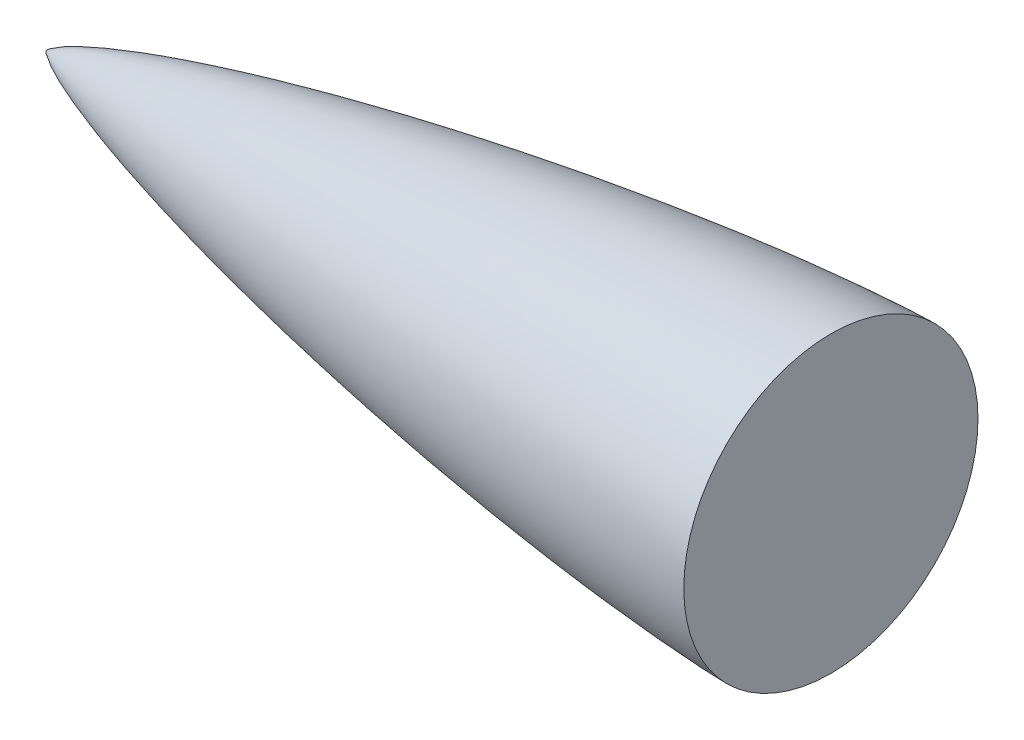
SolidWorks part; units mm, degrees
ref_plane "Front Plane" through (0, 0, 0) normal (0, 0, 1) x (1, 0, 0)
ref_plane "Top Plane" through (0, 0, 0) normal (0, 1, 0) x (1, 0, 0)
ref_plane "Right Plane" through (0, 0, 0) normal (1, 0, 0) x (0, 0, -1)
sketch "Sketch6" plane through (0, 0, 0) normal (0, 0, 1) x (1, 0, 0)
  line L0 (0, 0) -> (16, 0)
  line L1 (16, 3) -> (16, 0)
  spline S0 degree 4 poles (0, 0) (0.0011, 0.003) (0.0037, 0.008) (0.0089, 0.0143) (0.0169, 0.0231) (0.0278, 0.0335) (0.045, 0.0482) (0.0748, 0.0705) (0.127, 0.105) (0.2196, 0.1582) (0.3826, 0.2396) (0.6522, 0.3563) (1.1165, 0.5311) (1.785, 0.7482) (2.6259, 0.9882) (3.5978, 1.2355) (4.6, 1.467) (5.8578, 1.7335) (7.121, 1.9736) (8.3883, 2.1908) (9.6591, 2.386) (10.6776, 2.529) (11.698, 2.6584) (12.7201, 2.7734) (13.744, 2.8721) (14.6919, 2.9459) (15.3845, 2.984) (15.8207, 2.9985) (16, 3) knots 0 0 0 0 0 0.000783 0.00139 0.001959 0.002923 0.004458 0.00691 0.011061 0.018197 0.030525 0.051411 0.082827 0.139382 0.202214 0.265045 0.327876 0.390707 0.516369 0.579201 0.642032 0.704863 0.767694 0.830525 0.893356 0.956188 1 1 1 1 1 construction
  spline S1 degree 4 poles (0, 0) (0.0011, 0.003) (0.0037, 0.008) (0.0089, 0.0143) (0.0169, 0.0231) (0.0278, 0.0335) (0.045, 0.0482) (0.0748, 0.0705) (0.127, 0.105) (0.2196, 0.1582) (0.3826, 0.2396) (0.6522, 0.3563) (1.1165, 0.5311) (1.785, 0.7482) (2.6259, 0.9882) (3.5978, 1.2355) (4.6, 1.467) (5.8578, 1.7335) (7.121, 1.9736) (8.3883, 2.1908) (9.6591, 2.386) (10.6776, 2.529) (11.698, 2.6584) (12.7201, 2.7734) (13.744, 2.8721) (14.6919, 2.9459) (15.3845, 2.984) (15.8207, 2.9985) (16, 3) knots 0 0 0 0 0 0.000783 0.00139 0.001959 0.002923 0.004458 0.00691 0.011061 0.018197 0.030525 0.051411 0.082827 0.139382 0.202214 0.265045 0.327876 0.390707 0.516369 0.579201 0.642032 0.704863 0.767694 0.830525 0.893356 0.956188 1 1 1 1 1
  dimension "D1" = 16
revolve "Revolve6" add sketch "Sketch6" angle 360 about L0
